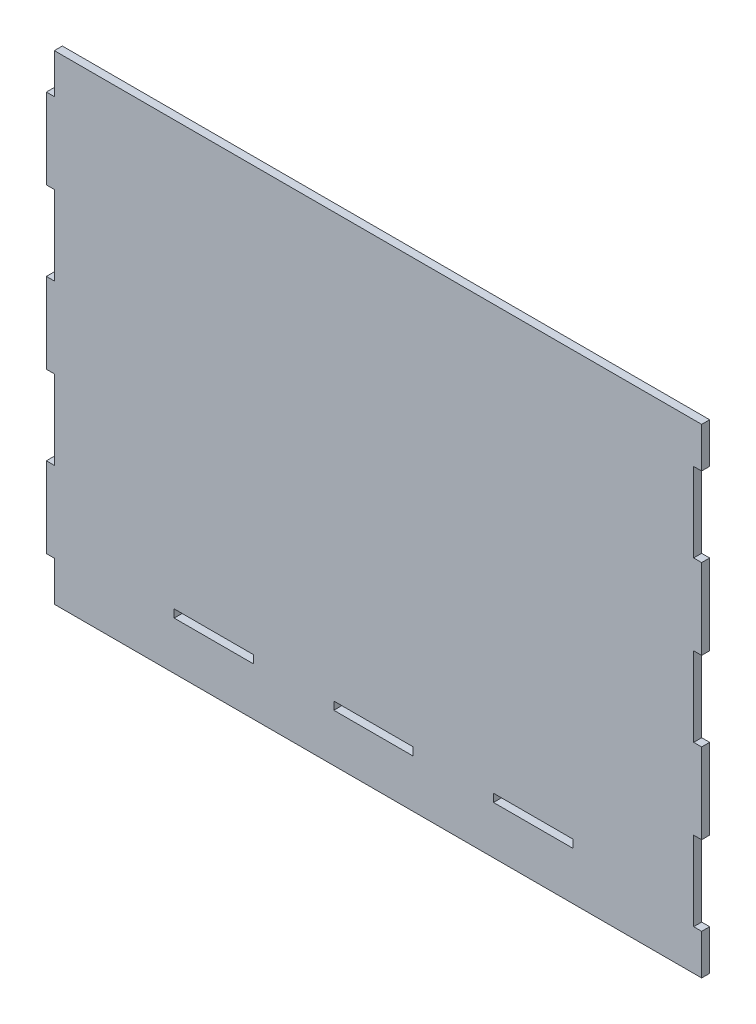
SolidWorks part; units mm, degrees
ref_plane "Ebene vorne" through (0, 0, 0) normal (0, 0, 1) x (1, 0, 0)
ref_plane "Ebene oben" through (0, 0, 0) normal (0, 1, 0) x (1, 0, 0)
ref_plane "Ebene rechts" through (0, 0, 0) normal (1, 0, 0) x (0, 0, -1)
sketch "Skizze1" plane through (0, 0, 0) normal (0, 0, 1) x (1, 0, 0)
  line L1 (0, 0) -> (410, 0)
  line L2 (0, 0) -> (0, 300)
  line L3 (0, 300) -> (410, 300)
  line L4 (410, 0) -> (410, 300)
  dimension "D1" = 410
  dimension "D2" = 300
extrude "Aufsatz-Linear austragen1" add sketch "Skizze1" along normal blind 5
sketch "Skizze2" plane through (0, 0, 5) normal (0, 0, 1) x (1, 0, 0)
  line L0 (410, 300) -> (0, 300) construction
  line L1 (-41.676, 324.65) -> (5, 324.65)
  line L2 (-41.676, 324.65) -> (-41.676, 275.05)
  line L3 (-41.676, 275.05) -> (5, 275.05)
  line L4 (5, 324.65) -> (5, 275.05)
  dimension "D1" = 49.6
  dimension "D3" = 5
  dimension "D4" = 24.95
extrude "Schnitt-Linear austragen1" cut sketch "Skizze2" against normal blind 5
pattern_linear "Lineares Muster1" count 4 spacing 99.9 along (0, -1, 0) of "Schnitt-Linear austragen1"
ref_plane "Ebene1" through (0, 150, 0) normal (0, 1, 0) x (1, 0, 0)
sketch "Skizze3" plane through (0, 0, 5) normal (0, 0, 1) x (1, 0, 0)
  line L1 (405, 274.7) -> (432.6636, 274.7)
  line L2 (405, 274.7) -> (405, 225.1)
  line L3 (405, 225.1) -> (432.6636, 225.1)
  line L4 (432.6636, 274.7) -> (432.6636, 225.1)
  dimension "D1" = 49.6
  dimension "D2" = 5
  dimension "D3" = 25.3
extrude "Schnitt-Linear austragen2" cut sketch "Skizze3" against normal blind 5
pattern_linear "Lineares Muster2" count 3 spacing 99.9 along (0, -1, 0) of "Schnitt-Linear austragen2"
sketch "Skizze4" plane through (0, 0, 5) normal (0, 0, 1) x (1, 0, 0)
  line L1 (0, 75.25) -> (0, 24.95) construction
  line L2 (79.95, 35) -> (129.55, 35)
  line L3 (79.95, 35) -> (79.95, 30)
  line L4 (79.95, 30) -> (129.55, 30)
  line L5 (129.55, 35) -> (129.55, 30)
  line L6 (5, 0) -> (410, 0) construction
  dimension "D1" = 79.95
  dimension "D2" = 5
  dimension "D3" = 49.6
  dimension "D4" = 30
extrude "Schnitt-Linear austragen3" cut sketch "Skizze4" against normal blind 5
pattern_linear "Lineares Muster3" count 3 spacing 99.9 along (1, 0, 0) of "Schnitt-Linear austragen3"
sketch "Skizze5" plane through (0, 0, 5) normal (0, 0, 1) x (1, 0, 0)
  line L0 (0, 160) -> (405, 160)
  line L2 (0, 175.15) -> (0, 124.85) construction
  line L3 (405, 174.8) -> (405, 125.2) construction
  line L4 (5, 0) -> (410, 0) construction
  line L5 (0, 160) -> (-27.8258, 200.4922)
  line L8 (-27.8258, 200.4922) -> (-27.8258, 333.8243)
  line L9 (-27.8258, 333.8243) -> (496.6631, 346.3375)
  line L10 (496.6631, 346.3375) -> (405, 160)
  line L11 (152.3495, 134.0111) -> (249.3866, 134.0111) construction
  line L12 (152.3495, 144.4612) -> (249.3866, 144.4612)
  line L13 (152.3495, 123.5609) -> (249.3866, 123.5609)
  arc A0 (152.3495, 144.4612) -> (152.3495, 123.5609) centre (152.3495, 134.0111) ccw
  arc A1 (249.3866, 123.5609) -> (249.3866, 144.4612) centre (249.3866, 134.0111) ccw
  point P13 (200.8681, 134.0111)
  dimension "D1" = 160
extrude "Schnitt-Linear austragen4" [suppressed] cut sketch "Skizze5" against normal blind 5
